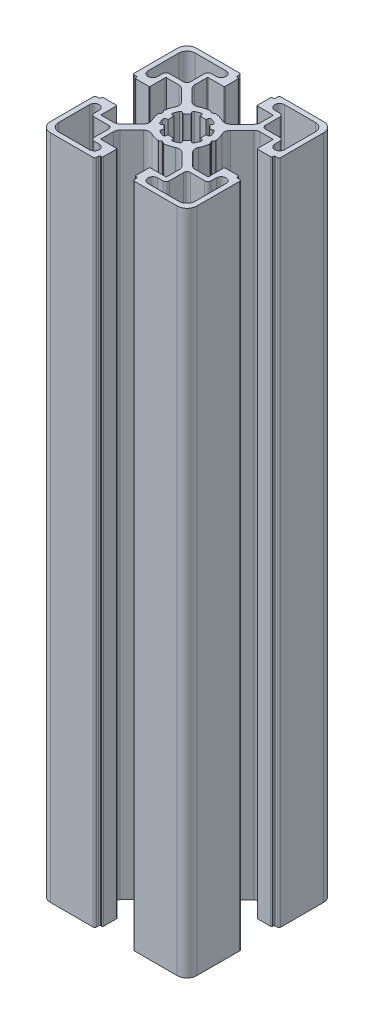
SolidWorks part; units mm, degrees
ref_plane "Front Plane" through (0, 0, 0) normal (0, 0, 1) x (1, 0, 0)
ref_plane "Top Plane" through (0, 0, 0) normal (0, 1, 0) x (1, 0, 0)
ref_plane "Right Plane" through (0, 0, 0) normal (1, 0, 0) x (0, 0, -1)
sketch "Sketch1" plane through (0, 0, 0) normal (0, 1, 0) x (1, 0, 0)
  line L106 (-18, 9.0002) -> (-18, 10.55)
  line L107 (-21, 18.5) -> (-21, 9.0002)
  line L108 (-9, 21) -> (-18.5, 21)
  line L109 (-10.55, 18) -> (-9, 18)
  line L110 (0.9675, 5.4811) -> (0.8674, 4.9242)
  line L111 (2.864, 4.0985) -> (3.1913, 4.5626)
  line L112 (4.5668, 3.2081) -> (4.0897, 2.8765)
  line L113 (4.9205, 0.8878) -> (5.4897, 0.9862)
  line L114 (5.4898, -0.9862) -> (4.9205, -0.8878)
  line L115 (4.0897, -2.8765) -> (4.5668, -3.2082)
  line L116 (3.1914, -4.5627) -> (2.864, -4.0985)
  line L117 (0.8674, -4.9242) -> (0.9675, -5.4811)
  line L118 (-0.9675, -5.4811) -> (-0.8674, -4.9242)
  line L119 (-2.864, -4.0985) -> (-3.1913, -4.5626)
  line L120 (-4.5668, -3.2082) -> (-4.0897, -2.8765)
  line L121 (-4.9205, -0.8878) -> (-5.4897, -0.9862)
  line L122 (-5.4899, 0.9862) -> (-4.9205, 0.8878)
  line L123 (-4.0897, 2.8765) -> (-4.5668, 3.2081)
  line L124 (-3.1914, 4.5627) -> (-2.864, 4.0985)
  line L125 (-0.8674, 4.9242) -> (-0.9675, 5.4811)
  line L126 (-11.55, 12.55) -> (-11.55, 17)
  line L127 (-17, 11.55) -> (-12.55, 11.55)
  line L128 (-21, -9.0002) -> (-21, -18.5)
  line L129 (-18, -10.55) -> (-18, -9.0002)
  line L130 (-12.55, -11.55) -> (-17, -11.55)
  line L131 (-11.55, -17) -> (-11.55, -12.55)
  line L132 (-9, -18) -> (-10.55, -18)
  line L133 (-18.5, -21) -> (-9, -21)
  line L134 (21, 9.0002) -> (21, 18.5)
  line L135 (18, 10.55) -> (18, 9.0002)
  line L136 (12.55, 11.55) -> (17, 11.55)
  line L137 (11.55, 17) -> (11.55, 12.55)
  line L138 (9, 18) -> (10.55, 18)
  line L139 (18.5, 21) -> (9, 21)
  line L140 (17, -11.55) -> (12.55, -11.55)
  line L141 (18, -9.0002) -> (18, -10.55)
  line L142 (21, -18.5) -> (21, -9.0002)
  line L143 (9, -21) -> (18.5, -21)
  line L144 (10.55, -18) -> (9, -18)
  line L145 (11.55, -12.55) -> (11.55, -17)
  line L146 (7.5635, 5.8587) -> (11.1298, 9.425)
  line L147 (12.5048, 9.9945) -> (16.3169, 9.9945)
  line L148 (16.5169, 9.7945) -> (16.5169, 5.2)
  line L149 (16.7169, 5) -> (20.7196, 5)
  line L150 (21.0196, 5.3) -> (21.0196, 5.5)
  line L151 (21.3196, 5.8) -> (22, 5.8)
  line L152 (22.5, 6.3) -> (22.5, 19.5)
  line L153 (19.5, 22.5) -> (6.3757, 22.5)
  line L154 (5.8757, 22) -> (5.8757, 21.3)
  line L155 (5.5757, 21) -> (5.3, 21)
  line L156 (5, 20.7) -> (5, 16.6668)
  line L157 (5.2, 16.4668) -> (9.9054, 16.4668)
  line L158 (10.1054, 16.2668) -> (10.1054, 12.4716)
  line L159 (9.5196, 11.0574) -> (5.9449, 7.4827)
  line L160 (0.7548, 7.9748) -> (0.1126, 7.6069)
  line L161 (-0.1126, 7.6069) -> (-0.7547, 7.9748)
  line L162 (-5.9449, 7.4827) -> (-9.5196, 11.0574)
  line L163 (-10.1054, 12.4716) -> (-10.1054, 16.2668)
  line L164 (-9.9054, 16.4668) -> (-5.2, 16.4668)
  line L165 (-5, 16.6668) -> (-5, 20.7)
  line L166 (-5.3, 21) -> (-5.5757, 21)
  line L167 (-5.8757, 21.3) -> (-5.8757, 22)
  line L168 (-6.3757, 22.5) -> (-19.5, 22.5)
  line L169 (-22.5, 19.5) -> (-22.5, 6.3)
  line L170 (-22, 5.8) -> (-21.3196, 5.8)
  line L171 (-21.0196, 5.5) -> (-21.0196, 5.3)
  line L172 (-20.7196, 5) -> (-16.7169, 5)
  line L173 (-16.5169, 5.2) -> (-16.5169, 9.7945)
  line L174 (-16.3169, 9.9945) -> (-12.5048, 9.9945)
  line L175 (-11.1298, 9.425) -> (-7.5635, 5.8587)
  line L176 (-7.974, 0.7926) -> (-7.5401, 0.0468)
  line L177 (-7.5401, -0.0468) -> (-7.974, -0.7926)
  line L178 (-7.5635, -5.8587) -> (-11.1298, -9.425)
  line L179 (-12.5048, -9.9945) -> (-16.3169, -9.9945)
  line L180 (-16.5169, -9.7945) -> (-16.5169, -5.2)
  line L181 (-16.7169, -5) -> (-20.7196, -5)
  line L182 (-21.0196, -5.3) -> (-21.0196, -5.5)
  line L183 (-21.3196, -5.8) -> (-22, -5.8)
  line L184 (-22.5, -6.3) -> (-22.5, -19.5)
  line L185 (-19.5, -22.5) -> (-6.3757, -22.5)
  line L186 (-5.8757, -22) -> (-5.8757, -21.3)
  line L187 (-5.5757, -21) -> (-5.3, -21)
  line L188 (-5, -20.7) -> (-5, -16.6668)
  line L189 (-5.2, -16.4668) -> (-9.9054, -16.4668)
  line L190 (-10.1054, -16.2668) -> (-10.1054, -12.4716)
  line L191 (-9.5196, -11.0574) -> (-5.9449, -7.4827)
  line L192 (-0.7547, -7.9748) -> (-0.1126, -7.6069)
  line L193 (0.1126, -7.6069) -> (0.7548, -7.9748)
  line L194 (5.9449, -7.4827) -> (9.5196, -11.0574)
  line L195 (10.1054, -12.4716) -> (10.1054, -16.2668)
  line L196 (9.9054, -16.4668) -> (5.2, -16.4668)
  line L197 (5, -16.6668) -> (5, -20.7)
  line L198 (5.3, -21) -> (5.5757, -21)
  line L199 (5.8757, -21.3) -> (5.8757, -22)
  line L200 (6.3757, -22.5) -> (19.5, -22.5)
  line L201 (22.5, -19.5) -> (22.5, -6.3)
  line L202 (22, -5.8) -> (21.3196, -5.8)
  line L203 (21.0196, -5.5) -> (21.0196, -5.3)
  line L204 (20.7196, -5) -> (16.7169, -5)
  line L205 (16.5169, -5.2) -> (16.5169, -9.7945)
  line L206 (16.3169, -9.9945) -> (12.5048, -9.9945)
  line L207 (11.1298, -9.425) -> (7.5635, -5.8587)
  line L208 (7.974, -0.7926) -> (7.5401, -0.0468)
  line L209 (7.5401, 0.0468) -> (7.974, 0.7926)
  arc A140 (-17, 11.55) -> (-18, 10.55) centre (-17, 10.55) ccw
  arc A141 (-21, 9.0002) -> (-18, 9.0002) centre (-19.5, 9.0002) ccw
  arc A142 (-18.5, 21) -> (-21, 18.5) centre (-18.5, 18.5) ccw
  arc A143 (-9, 18) -> (-9, 21) centre (-9, 19.5) ccw
  arc A144 (-10.55, 18) -> (-11.55, 17) centre (-10.55, 17) ccw
  arc A145 (-12.55, 11.55) -> (-11.55, 12.55) centre (-12.55, 12.55) ccw
  arc A146 (-21, -18.5) -> (-18.5, -21) centre (-18.5, -18.5) ccw
  arc A147 (-18, -9.0002) -> (-21, -9.0002) centre (-19.5, -9.0002) ccw
  arc A148 (-18, -10.55) -> (-17, -11.55) centre (-17, -10.55) ccw
  arc A149 (-11.55, -12.55) -> (-12.55, -11.55) centre (-12.55, -12.55) ccw
  arc A150 (-11.55, -17) -> (-10.55, -18) centre (-10.55, -17) ccw
  arc A151 (-9, -21) -> (-9, -18) centre (-9, -19.5) ccw
  arc A152 (0.8674, 4.9242) -> (-0.8674, 4.9242) centre (0, 0) ccw
  arc A153 (1.5951, 5.8941) -> (0.9675, 5.4811) centre (1.4627, 5.4119) ccw
  arc A154 (3.0417, 5.301) -> (1.5951, 5.8941) centre (0.0235, 0) ccw
  arc A155 (3.1913, 4.5626) -> (3.0417, 5.301) centre (2.7943, 4.8665) ccw
  arc A156 (4.0897, 2.8765) -> (2.864, 4.0985) centre (0, 0) ccw
  arc A157 (5.3025, 3.0565) -> (4.5668, 3.2081) centre (4.868, 2.8091) ccw
  arc A158 (5.906, 1.6142) -> (5.3025, 3.0565) centre (0.0235, 0) ccw
  arc A159 (5.4897, 0.9862) -> (5.906, 1.6142) centre (5.4239, 1.4819) ccw
  arc A160 (4.9205, -0.8878) -> (4.9205, 0.8878) centre (0, 0) ccw
  arc A161 (5.906, -1.6142) -> (5.4898, -0.9862) centre (5.4239, -1.4819) ccw
  arc A162 (5.3025, -3.0564) -> (5.906, -1.6142) centre (0.0235, 0) ccw
  arc A163 (4.5668, -3.2082) -> (5.3025, -3.0564) centre (4.868, -2.8091) ccw
  arc A164 (2.864, -4.0985) -> (4.0897, -2.8765) centre (0, 0) ccw
  arc A165 (3.0416, -5.301) -> (3.1914, -4.5627) centre (2.7943, -4.8665) ccw
  arc A166 (1.5951, -5.8941) -> (3.0416, -5.301) centre (0.0235, 0) ccw
  arc A167 (0.9675, -5.4811) -> (1.5951, -5.8941) centre (1.4627, -5.4119) ccw
  arc A168 (-0.8674, -4.9242) -> (0.8674, -4.9242) centre (0, 0) ccw
  arc A169 (-1.5951, -5.8941) -> (-0.9675, -5.4811) centre (-1.4627, -5.4119) ccw
  arc A170 (-3.0416, -5.301) -> (-1.5951, -5.8941) centre (-0.0235, 0) ccw
  arc A171 (-3.1913, -4.5626) -> (-3.0416, -5.301) centre (-2.7943, -4.8665) ccw
  arc A172 (-4.0897, -2.8765) -> (-2.864, -4.0985) centre (0, 0) ccw
  arc A173 (-5.3025, -3.0565) -> (-4.5668, -3.2082) centre (-4.868, -2.8091) ccw
  arc A174 (-5.906, -1.6142) -> (-5.3025, -3.0565) centre (-0.0235, 0) ccw
  arc A175 (-5.4897, -0.9862) -> (-5.906, -1.6142) centre (-5.4239, -1.4819) ccw
  arc A176 (-4.9205, 0.8878) -> (-4.9205, -0.8878) centre (0, 0) ccw
  arc A177 (-5.906, 1.6141) -> (-5.4899, 0.9862) centre (-5.4239, 1.4818) ccw
  arc A178 (-5.3025, 3.0564) -> (-5.906, 1.6141) centre (-0.0235, 0) ccw
  arc A179 (-4.5668, 3.2081) -> (-5.3025, 3.0564) centre (-4.868, 2.8091) ccw
  arc A180 (-2.864, 4.0985) -> (-4.0897, 2.8765) centre (0, 0) ccw
  arc A181 (-3.0417, 5.301) -> (-3.1914, 4.5627) centre (-2.7943, 4.8665) ccw
  arc A182 (-1.5951, 5.8941) -> (-3.0417, 5.301) centre (-0.0235, 0) ccw
  arc A183 (-0.9675, 5.4811) -> (-1.5951, 5.8941) centre (-1.4627, 5.4119) ccw
  arc A184 (21, 18.5) -> (18.5, 21) centre (18.5, 18.5) ccw
  arc A185 (18, 9.0002) -> (21, 9.0002) centre (19.5, 9.0002) ccw
  arc A186 (18, 10.55) -> (17, 11.55) centre (17, 10.55) ccw
  arc A187 (11.55, 12.55) -> (12.55, 11.55) centre (12.55, 12.55) ccw
  arc A188 (11.55, 17) -> (10.55, 18) centre (10.55, 17) ccw
  arc A189 (9, 21) -> (9, 18) centre (9, 19.5) ccw
  arc A190 (12.55, -11.55) -> (11.55, -12.55) centre (12.55, -12.55) ccw
  arc A191 (17, -11.55) -> (18, -10.55) centre (17, -10.55) ccw
  arc A192 (21, -9.0002) -> (18, -9.0002) centre (19.5, -9.0002) ccw
  arc A193 (18.5, -21) -> (21, -18.5) centre (18.5, -18.5) ccw
  arc A194 (9, -18) -> (9, -21) centre (9, -19.5) ccw
  arc A195 (10.55, -18) -> (11.55, -17) centre (10.55, -17) ccw
  arc A196 (7.9999, 0.9154) -> (7.2004, 3.6119) centre (0.0496, 0.0249) ccw
  arc A197 (7.5635, 5.8587) -> (7.2004, 3.6119) centre (8.9385, 4.4837) ccw
  arc A198 (12.5048, 9.9945) -> (11.1298, 9.425) centre (12.5048, 8.05) ccw
  arc A199 (16.5169, 9.7945) -> (16.3169, 9.9945) centre (16.3169, 9.7945) ccw
  arc A200 (16.5169, 5.2) -> (16.7169, 5) centre (16.7169, 5.2) ccw
  arc A201 (20.7196, 5) -> (21.0196, 5.3) centre (20.7196, 5.3) ccw
  arc A202 (21.3196, 5.8) -> (21.0196, 5.5) centre (21.3196, 5.5) ccw
  arc A203 (22, 5.8) -> (22.5, 6.3) centre (22, 6.3) ccw
  arc A204 (22.5, 19.5) -> (19.5, 22.5) centre (19.5, 19.5) ccw
  arc A205 (6.3757, 22.5) -> (5.8757, 22) centre (6.3757, 22) ccw
  arc A206 (5.5757, 21) -> (5.8757, 21.3) centre (5.5757, 21.3) ccw
  arc A207 (5.3, 21) -> (5, 20.7) centre (5.3, 20.7) ccw
  arc A208 (5, 16.6668) -> (5.2, 16.4668) centre (5.2, 16.6668) ccw
  arc A209 (10.1054, 16.2668) -> (9.9054, 16.4668) centre (9.9054, 16.2668) ccw
  arc A210 (9.5196, 11.0574) -> (10.1054, 12.4716) centre (8.1054, 12.4716) ccw
  arc A211 (3.6665, 7.1733) -> (5.9449, 7.4827) centre (4.5855, 8.9496) ccw
  arc A212 (3.6665, 7.1733) -> (0.8753, 8.0001) centre (0.0235, 0) ccw
  arc A213 (0.8753, 8.0001) -> (0.7548, 7.9748) centre (0.8542, 7.8013) ccw
  arc A214 (0, 7.531) -> (0.1126, 7.6069) centre (-0.0489, 7.7249) ccw
  arc A215 (-0.1126, 7.6069) -> (0, 7.531) centre (0.0489, 7.7249) ccw
  arc A216 (-0.7547, 7.9748) -> (-0.8753, 8.0001) centre (-0.8542, 7.8013) ccw
  arc A217 (-0.8753, 8.0001) -> (-3.6665, 7.1733) centre (-0.0235, 0) ccw
  arc A218 (-5.9449, 7.4827) -> (-3.6665, 7.1733) centre (-4.5855, 8.9496) ccw
  arc A219 (-10.1054, 12.4716) -> (-9.5196, 11.0574) centre (-8.1054, 12.4716) ccw
  arc A220 (-9.9054, 16.4668) -> (-10.1054, 16.2668) centre (-9.9054, 16.2668) ccw
  arc A221 (-5.2, 16.4668) -> (-5, 16.6668) centre (-5.2, 16.6668) ccw
  arc A222 (-5, 20.7) -> (-5.3, 21) centre (-5.3, 20.7) ccw
  arc A223 (-5.8757, 21.3) -> (-5.5757, 21) centre (-5.5757, 21.3) ccw
  arc A224 (-5.8757, 22) -> (-6.3757, 22.5) centre (-6.3757, 22) ccw
  arc A225 (-19.5, 22.5) -> (-22.5, 19.5) centre (-19.5, 19.5) ccw
  arc A226 (-22.5, 6.3) -> (-22, 5.8) centre (-22, 6.3) ccw
  arc A227 (-21.0196, 5.5) -> (-21.3196, 5.8) centre (-21.3196, 5.5) ccw
  arc A228 (-21.0196, 5.3) -> (-20.7196, 5) centre (-20.7196, 5.3) ccw
  arc A229 (-16.7169, 5) -> (-16.5169, 5.2) centre (-16.7169, 5.2) ccw
  arc A230 (-16.3169, 9.9945) -> (-16.5169, 9.7945) centre (-16.3169, 9.7945) ccw
  arc A231 (-11.1298, 9.425) -> (-12.5048, 9.9945) centre (-12.5048, 8.05) ccw
  arc A232 (-7.2004, 3.6119) -> (-7.5635, 5.8587) centre (-8.9385, 4.4837) ccw
  arc A233 (-7.2004, 3.6119) -> (-7.9999, 0.9154) centre (-0.0496, 0.0249) ccw
  arc A234 (-7.9999, 0.9154) -> (-7.974, 0.7926) centre (-7.8011, 0.8932) ccw
  arc A235 (-7.5313, 0) -> (-7.5401, 0.0468) centre (-7.7309, -0.013) ccw
  arc A236 (-7.5401, -0.0468) -> (-7.5313, 0) centre (-7.7309, 0.013) ccw
  arc A237 (-7.974, -0.7926) -> (-7.9999, -0.9154) centre (-7.8011, -0.8932) ccw
  arc A238 (-7.9999, -0.9154) -> (-7.2004, -3.6119) centre (-0.0496, -0.0249) ccw
  arc A239 (-7.5635, -5.8587) -> (-7.2004, -3.6119) centre (-8.9385, -4.4837) ccw
  arc A240 (-12.5048, -9.9945) -> (-11.1298, -9.425) centre (-12.5048, -8.05) ccw
  arc A241 (-16.5169, -9.7945) -> (-16.3169, -9.9945) centre (-16.3169, -9.7945) ccw
  arc A242 (-16.5169, -5.2) -> (-16.7169, -5) centre (-16.7169, -5.2) ccw
  arc A243 (-20.7196, -5) -> (-21.0196, -5.3) centre (-20.7196, -5.3) ccw
  arc A244 (-21.3196, -5.8) -> (-21.0196, -5.5) centre (-21.3196, -5.5) ccw
  arc A245 (-22, -5.8) -> (-22.5, -6.3) centre (-22, -6.3) ccw
  arc A246 (-22.5, -19.5) -> (-19.5, -22.5) centre (-19.5, -19.5) ccw
  arc A247 (-6.3757, -22.5) -> (-5.8757, -22) centre (-6.3757, -22) ccw
  arc A248 (-5.5757, -21) -> (-5.8757, -21.3) centre (-5.5757, -21.3) ccw
  arc A249 (-5.3, -21) -> (-5, -20.7) centre (-5.3, -20.7) ccw
  arc A250 (-5, -16.6668) -> (-5.2, -16.4668) centre (-5.2, -16.6668) ccw
  arc A251 (-10.1054, -16.2668) -> (-9.9054, -16.4668) centre (-9.9054, -16.2668) ccw
  arc A252 (-9.5196, -11.0574) -> (-10.1054, -12.4716) centre (-8.1054, -12.4716) ccw
  arc A253 (-3.6665, -7.1733) -> (-5.9449, -7.4827) centre (-4.5855, -8.9496) ccw
  arc A254 (-3.6665, -7.1733) -> (-0.8753, -8.0001) centre (-0.0235, 0) ccw
  arc A255 (-0.8753, -8.0001) -> (-0.7547, -7.9748) centre (-0.8542, -7.8013) ccw
  arc A256 (0, -7.531) -> (-0.1126, -7.6069) centre (0.0489, -7.7249) ccw
  arc A257 (0.1126, -7.6069) -> (0, -7.531) centre (-0.0489, -7.7249) ccw
  arc A258 (0.7548, -7.9748) -> (0.8753, -8.0001) centre (0.8542, -7.8012) ccw
  arc A259 (0.8753, -8.0001) -> (3.6665, -7.1733) centre (0.0235, 0) ccw
  arc A260 (5.9449, -7.4827) -> (3.6665, -7.1733) centre (4.5855, -8.9496) ccw
  arc A261 (10.1054, -12.4716) -> (9.5196, -11.0574) centre (8.1054, -12.4716) ccw
  arc A262 (9.9054, -16.4668) -> (10.1054, -16.2668) centre (9.9054, -16.2668) ccw
  arc A263 (5.2, -16.4668) -> (5, -16.6668) centre (5.2, -16.6668) ccw
  arc A264 (5, -20.7) -> (5.3, -21) centre (5.3, -20.7) ccw
  arc A265 (5.8757, -21.3) -> (5.5757, -21) centre (5.5757, -21.3) ccw
  arc A266 (5.8757, -22) -> (6.3757, -22.5) centre (6.3757, -22) ccw
  arc A267 (19.5, -22.5) -> (22.5, -19.5) centre (19.5, -19.5) ccw
  arc A268 (22.5, -6.3) -> (22, -5.8) centre (22, -6.3) ccw
  arc A269 (21.0196, -5.5) -> (21.3196, -5.8) centre (21.3196, -5.5) ccw
  arc A270 (21.0196, -5.3) -> (20.7196, -5) centre (20.7196, -5.3) ccw
  arc A271 (16.7169, -5) -> (16.5169, -5.2) centre (16.7169, -5.2) ccw
  arc A272 (16.3169, -9.9945) -> (16.5169, -9.7945) centre (16.3169, -9.7945) ccw
  arc A273 (11.1298, -9.425) -> (12.5048, -9.9945) centre (12.5048, -8.05) ccw
  arc A274 (7.2004, -3.6119) -> (7.5635, -5.8587) centre (8.9385, -4.4837) ccw
  arc A275 (7.2004, -3.6119) -> (7.9999, -0.9154) centre (0.0496, -0.0249) ccw
  arc A276 (7.9999, -0.9154) -> (7.974, -0.7926) centre (7.8011, -0.8932) ccw
  arc A277 (7.5313, 0) -> (7.5401, -0.0468) centre (7.7309, 0.013) ccw
  arc A278 (7.5401, 0.0468) -> (7.5313, 0) centre (7.7309, -0.013) ccw
  arc A279 (7.974, 0.7926) -> (7.9999, 0.9154) centre (7.8011, 0.8932) ccw
extrude "Boss-Extrude1" add sketch "Sketch1" along normal blind 205
